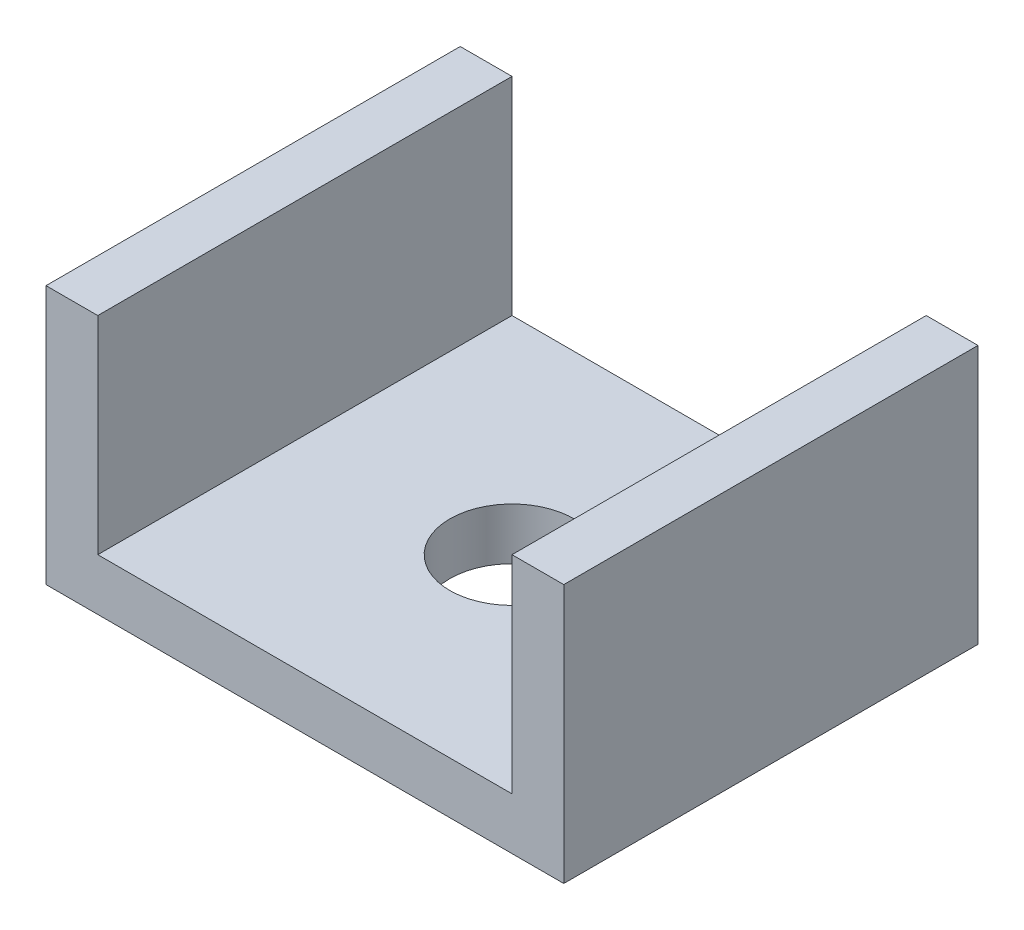
SolidWorks part; units mm, degrees
ref_plane "Front Plane" through (0, 0, 0) normal (0, 0, 1) x (1, 0, 0)
ref_plane "Top Plane" through (0, 0, 0) normal (0, 1, 0) x (1, 0, 0)
ref_plane "Right Plane" through (0, 0, 0) normal (1, 0, 0) x (0, 0, -1)
sketch "Sketch2" plane through (0, 0, 0) normal (0, 0, 1) x (1, 0, 0)
  line L0 (0, 32.4416) -> (0, -18.1069) construction
  line L1 (15.875, 0) -> (-15.875, 0)
  line L2 (-15.875, 0) -> (-15.875, 15.875)
  line L3 (-15.875, 15.875) -> (-12.7, 15.875)
  line L4 (-12.7, 15.875) -> (-12.7, 3.175)
  line L5 (-12.7, 3.175) -> (12.7, 3.175)
  line L6 (12.7, 15.875) -> (12.7, 3.175)
  line L7 (15.875, 15.875) -> (12.7, 15.875)
  line L8 (15.875, 0) -> (15.875, 15.875)
  point P10 (0, 3.175)
  point P13 (0, 0)
  dimension "D1" = 12.7
  dimension "D2" = 3.175
  dimension "D3" = 3.175
  dimension "D4" = 12.7
extrude "Boss-Extrude1" add sketch "Sketch2" along normal blind 25.4
sketch "Sketch3" plane through (0, 3.175, 0) normal (0, 1, 0) x (1, 0, 0)
  line L0 (-15.875, -12.7) -> (15.875, -12.7) construction
  line L2 (-15.875, -25.4) -> (-15.875, 0) construction
  line L3 (15.875, -25.4) -> (15.875, 0) construction
  circle A0 centre (0, -12.7) radius 3.81
  dimension "D1" = 7.62
extrude "Cut-Extrude1" cut sketch "Sketch3" against normal through all
